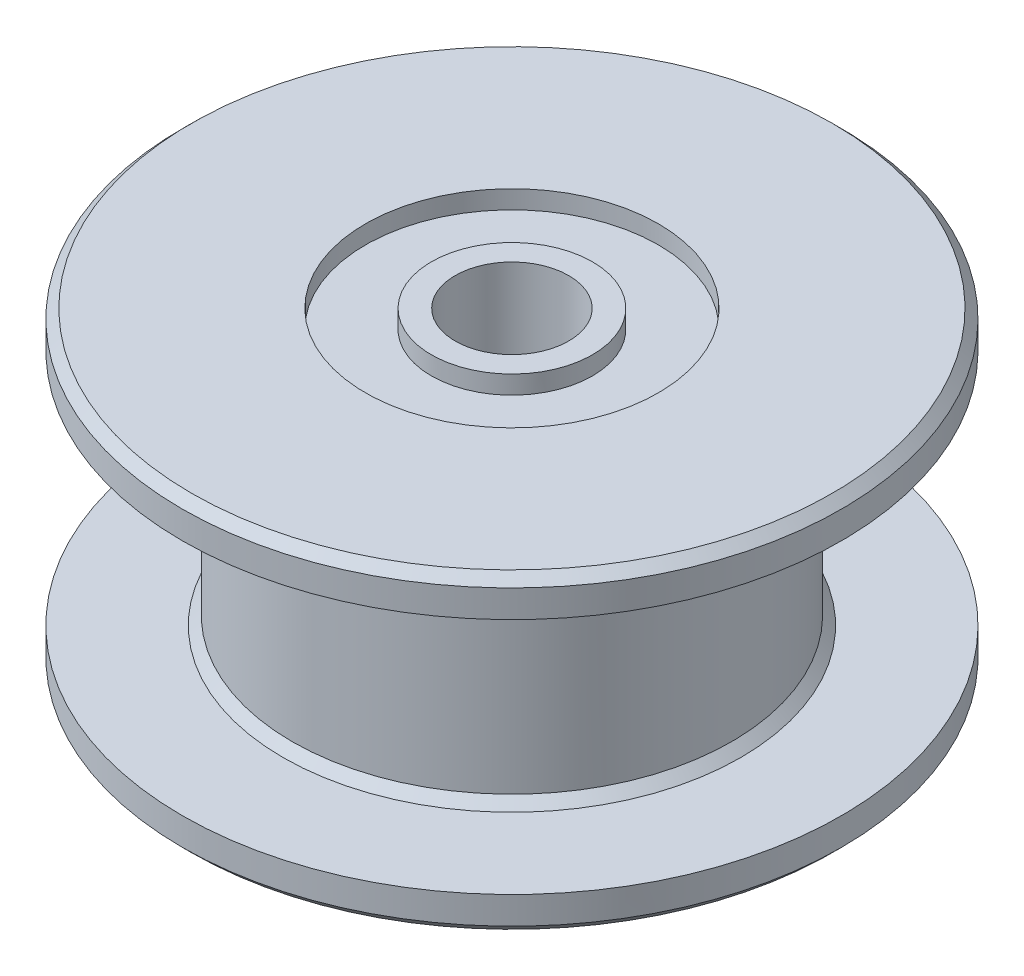
SolidWorks part; units mm, degrees
material "1060 Alloy"
ref_plane "Front Plane" through (0, 0, 0) normal (0, 0, 1) x (1, 0, 0)
ref_plane "Top Plane" through (0, 0, 0) normal (0, 1, 0) x (1, 0, 0)
ref_plane "Right Plane" through (0, 0, 0) normal (1, 0, 0) x (0, 0, -1)
sketch "Sketch1" plane through (0, 0, 0) normal (0, 0, 1) x (1, 0, 0)
  line L0 (0, 0) -> (-9, 0)
  line L1 (-9, 0) -> (-9, 1)
  line L2 (-9, 1) -> (-6, 1)
  line L3 (-6, 1) -> (-6, 7.5)
  line L4 (-6, 7.5) -> (-9, 7.5)
  line L5 (-9, 7.5) -> (-9, 8.5)
  line L6 (-9, 8.5) -> (0, 8.5)
  line L7 (0, 8.5) -> (0, 0) construction
  line L8 (0, 0) -> (0, 8.5)
  dimension "D1" = 8.5
  dimension "D2" = 1
  dimension "D3" = 1
  dimension "D4" = 9
  dimension "D5" = 6
revolve "Revolve1" add sketch "Sketch1" angle 360 about L7
ref_plane "Plane1" through (0, 4.25, 0) normal (0, 1, 0) x (1, 0, 0)
sketch "Sketch2" plane through (0, 0, 0) normal (0, -1, 0) x (1, 0, 0)
  circle A0 centre (0, 0) radius 4
extrude "Cut-Extrude1" cut sketch "Sketch2" against normal blind 0.5
sketch "Sketch3" plane through (0, 0.5, 0) normal (0, -1, 0) x (1, 0, 0)
  circle A0 centre (0, 0) radius 2.2
extrude "Boss-Extrude1" add sketch "Sketch3" along normal blind 0.5
mirror "Mirror1" about plane through (0, 4.25, 0) normal (0, 1, 0) of "Cut-Extrude1", "Boss-Extrude1"
sketch "Sketch4" plane through (0, 0, 0) normal (0, -1, 0) x (1, 0, 0)
  circle A0 centre (0, 0) radius 1.55
extrude "Cut-Extrude2" cut sketch "Sketch4" against normal through all
chamfer "Chamfer1" distance 0.25 4 edges at (0, 0, 9) (0, 1, 6) (0, 7.5, 6) (0, 8.5, 9)
